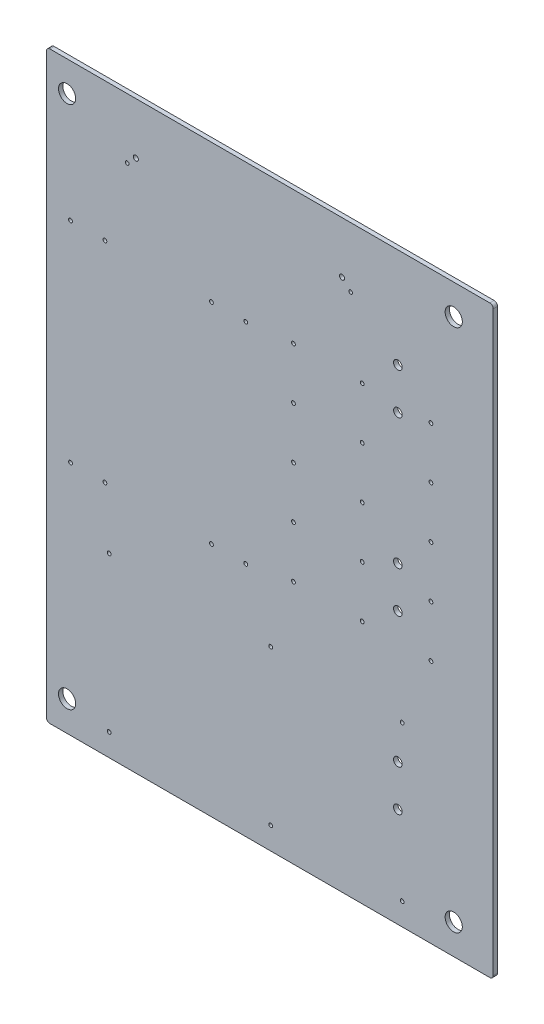
SolidWorks part; units mm, degrees
ref_plane "Front Plane" through (0, 0, 0) normal (0, 0, 1) x (1, 0, 0)
ref_plane "Top Plane" through (0, 0, 0) normal (0, 1, 0) x (1, 0, 0)
ref_plane "Right Plane" through (0, 0, 0) normal (1, 0, 0) x (0, 0, -1)
sketch "Sketch1" plane through (0, 0, 0) normal (0, 0, 1) x (1, 0, 0)
  line L0 (0, 0) -> (106.5527, 0) construction
  line L1 (-162.56, 215.9) -> (162.56, 215.9)
  line L2 (-165.1, 213.36) -> (-165.1, -213.36)
  line L3 (-162.56, -215.9) -> (162.56, -215.9)
  line L4 (165.1, 213.36) -> (165.1, -213.36)
  circle A0 centre (-149.86, 193.675) radius 6.35
  circle A1 centre (135.89, 193.675) radius 6.35
  circle A2 centre (135.89, -193.675) radius 6.35
  circle A3 centre (-149.86, -193.675) radius 6.35
  circle A4 centre (94.615, 127) radius 38.1 construction
  circle A5 centre (94.615, 0) radius 38.1 construction
  circle A6 centre (94.615, -127) radius 38.1 construction
  circle A7 centre (94.615, 142.24) radius 3.175
  circle A8 centre (94.615, 111.76) radius 3.175
  circle A9 centre (94.615, -15.24) radius 3.175
  circle A10 centre (94.615, 15.24) radius 3.175
  circle A11 centre (94.615, -142.24) radius 3.175
  circle A12 centre (94.615, -111.76) radius 3.175
  arc A13 (162.56, 215.9) -> (165.1, 213.36) centre (162.56, 213.36) cw
  arc A14 (-162.56, 215.9) -> (-165.1, 213.36) centre (-162.56, 213.36) ccw
  arc A15 (-165.1, -213.36) -> (-162.56, -215.9) centre (-162.56, -213.36) ccw
  arc A16 (162.56, -215.9) -> (165.1, -213.36) centre (162.56, -213.36) ccw
  circle A17 centre (53.34, 177.8) radius 1.8669
  circle A18 centre (-99.06, 177.8) radius 1.8669
  point P4 (0, 215.9)
  point P6 (-165.1, 0)
  point P37 (165.1, 215.9)
  point P40 (-165.1, 215.9)
  point P43 (-165.1, -215.9)
  dimension "D3" = 15.24
  dimension "D4" = 285.75
  dimension "D5" = 12.7
  dimension "D7" = 76.2
  dimension "D8" = 127
  dimension "D9" = 127
  dimension "D10" = 66.675
  dimension "D11" = 41.275
  dimension "D12" = 6.35
  dimension "D13" = 15.24
  dimension "D14" = 15.24
  dimension "D15" = 2.54
  dimension "D17" = 50.8
  dimension "D18" = 38.1
  dimension "D19" = 3.7338
  dimension "D1" = 330.2
  dimension "D2" = 431.8
  dimension "D6" = 193.675
  dimension "D16" = 152.4
extrude "Extrude1" add sketch "Sketch1" along normal blind 3.175
hole_wizard "#4-40 Tapped Hole1" positions "Sketch3" profile "Sketch2" tap size "#4-40" standard "Ansi Inch"
sketch "Sketch3" plane through (0, 0, 3.175) normal (0, 0, 1) x (1, 0, 0)
  line L0 (-43.18, -41.275) -> (-17.78, -41.275) construction
  circle A0 centre (-149.86, -193.675) radius 6.35 construction
  circle A1 centre (135.89, -193.675) radius 6.35 construction
  circle A2 centre (94.615, -142.24) radius 3.175 construction
  point P0 (-147.32, 113.665)
  point P1 (-43.18, 113.665)
  point P3 (-43.18, -41.275)
  point P5 (-147.32, -41.275)
  point P14 (-118.745, -85.09)
  point P16 (0.635, -85.09)
  point P18 (97.79, -85.09)
  point P20 (97.79, -199.39)
  point P22 (0.635, -199.39)
  point P24 (-118.745, -199.39)
  point P57 (-121.92, 113.665)
  point P58 (-17.78, 113.665)
  point P59 (-17.78, -41.275)
  point P60 (-121.92, -41.275)
  point P63 (17.4511, 117.3183)
  point P65 (68.2511, 117.3183)
  point P67 (119.0511, 117.3183)
  point P69 (17.4511, 79.2183)
  point P71 (17.4511, 41.1183)
  point P73 (68.2511, 79.2183)
  point P75 (119.0511, 79.2183)
  point P77 (119.0511, 41.1183)
  point P79 (68.2511, 41.1183)
  point P81 (17.4511, 3.0183)
  point P83 (68.2511, 3.0183)
  point P85 (119.0511, 3.0183)
  point P87 (119.0511, -35.0817)
  point P89 (68.2511, -35.0817)
  point P91 (17.4511, -35.0817)
  dimension "D4" = 2.54
  dimension "D8" = 38.1
  dimension "D9" = 57.15
  dimension "D1" = 104.14
  dimension "D2" = 154.94
  dimension "D3" = 152.4
  dimension "D5" = 119.38
  dimension "D6" = 97.155
  dimension "D7" = 114.3
  dimension "D10" = 25.4
  dimension "D11" = 50.8
  dimension "D12" = 50.8
  dimension "D13" = 38.1
  dimension "D14" = 38.1
  dimension "D15" = 38.1
  dimension "D16" = 38.1
sketch "Sketch2" plane through (-147.32, 113.665, 3.175) normal (1, 0, 0) x (0, -1, 0)
  line L0 (0, 0) -> (0, 9.5438)
  line L1 (0, 9.5438) -> (1.1303, 8.8646)
  line L2 (1.1303, 8.8646) -> (1.1303, 5.6896)
  line L3 (1.1303, 5.6896) -> (1.4224, 5.6896)
  line L4 (1.4224, 5.6896) -> (1.4224, 0)
  line L5 (1.4224, 0) -> (0, 0)
  line L10 (0, 9.5438) -> (-1.1303, 8.8646) construction
  line L11 (0, -6.35) -> (0, 107.95) construction
  dimension "Tap Drill Dia." = 2.2606
  dimension "Tap Drill Depth" = 8.8646
  dimension "Thread Major Dia." = 2.8448
  dimension "Thread Depth" = 5.6896
  dimension "Drill Angle" = 118
hole_wizard "#6-32 Tapped Hole1" positions "Sketch5" profile "Sketch4" tap size "#6-32" standard "Ansi Inch"
sketch "Sketch5" plane through (0, 0, 3.175) normal (0, 0, 1) x (1, 0, 0)
  circle A0 centre (-99.06, 177.8) radius 1.8669 construction
  point P0 (59.69, 171.45)
  point P1 (-105.41, 171.45)
  dimension "D1" = 6.35
  dimension "D2" = 165.1
  dimension "D3" = 6.35
sketch "Sketch4" plane through (59.69, 171.45, 3.175) normal (1, 0, 0) x (0, -1, 0)
  line L0 (0, 0) -> (0, 11.7347)
  line L1 (0, 11.7347) -> (1.3525, 10.922)
  line L2 (1.3525, 10.922) -> (1.3525, 0)
  line L5 (1.3525, 0) -> (0, 0)
  line L10 (0, 11.7347) -> (-1.3525, 10.922) construction
  line L11 (0, -6.35) -> (0, 107.95) construction
  dimension "Tap Drill Dia." = 2.7051
  dimension "Tap Drill Depth" = 10.922
  dimension "Drill Angle" = 118
cosmetic thread "Hole Thread1"
cosmetic thread "Hole Thread2"
